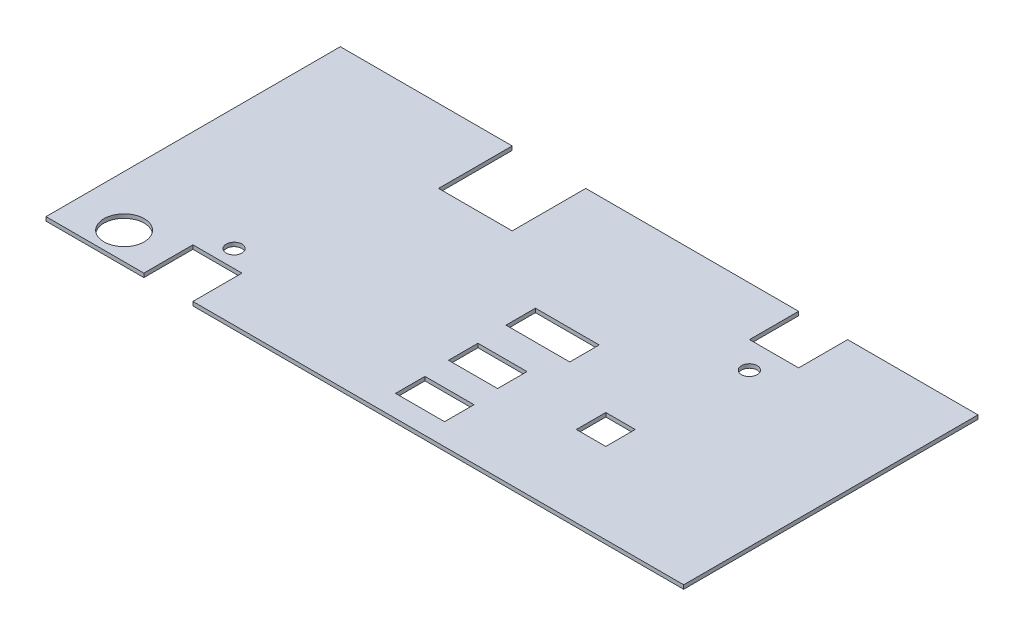
SolidWorks part; units mm, degrees
ref_plane "Front Plane" through (0, 0, 0) normal (0, 0, 1) x (1, 0, 0)
ref_plane "Top Plane" through (0, 0, 0) normal (0, 1, 0) x (1, 0, 0)
ref_plane "Right Plane" through (0, 0, 0) normal (1, 0, 0) x (0, 0, -1)
sketch "Sketch1" plane through (0, 0, 0) normal (0, 1, 0) x (1, 0, 0)
  line L1 (-65, 30) -> (65, 30)
  line L2 (-65, 30) -> (-65, -30)
  line L3 (-65, -30) -> (65, -30)
  line L4 (65, 30) -> (65, -30)
  line L5 (-65, 30) -> (65, -30) construction
  line L6 (-65, -30) -> (65, 30) construction
  point P0 (0, 0)
  dimension "D1" = 60
  dimension "D2" = 130
extrude "Boss-Extrude1" add sketch "Sketch1" along normal blind 0.8
sketch "Sketch2" plane through (0, 0, 0) normal (0, 1, 0) x (1, 0, 0)
  line L0 (-65, -30) -> (65, -30) construction
  line L1 (-45.0488, -20) -> (-35.0488, -20)
  line L2 (-45.0488, -20) -> (-45.0488, -30)
  line L3 (-45.0488, -30) -> (-35.0488, -30)
  line L4 (-35.0488, -20) -> (-35.0488, -30)
  line L5 (-45.0488, -20) -> (-35.0488, -30) construction
  line L6 (-45.0488, -30) -> (-35.0488, -20) construction
  line L7 (65, 30) -> (-65, 30) construction
  line L8 (28.4256, 30.0049) -> (38.4256, 30.0049)
  line L9 (28.4256, 30.0049) -> (28.4256, 20.0049)
  line L10 (28.4256, 20.0049) -> (38.4256, 20.0049)
  line L11 (38.4256, 30.0049) -> (38.4256, 20.0049)
  line L12 (28.4256, 30.0049) -> (38.4256, 20.0049) construction
  line L13 (28.4256, 20.0049) -> (38.4256, 30.0049) construction
  line L14 (-29.9609, 30) -> (-14.9609, 30)
  line L15 (-29.9609, 30) -> (-29.9609, 15)
  line L16 (-29.9609, 15) -> (-14.9609, 15)
  line L17 (-14.9609, 30) -> (-14.9609, 15)
  line L18 (-29.9609, 30) -> (-14.9609, 15) construction
  line L19 (-29.9609, 15) -> (-14.9609, 30) construction
  point P0 (-40.0488, -25)
  point P7 (33.4256, 25.0049)
  point P12 (-22.4609, 22.5)
  dimension "D1" = 15
  dimension "D2" = 15
  dimension "D3" = 10
  dimension "D4" = 10
  dimension "D5" = 10
  dimension "D6" = 10
extrude "Cut-Extrude5" cut sketch "Sketch2" along normal blind 3
sketch "Sketch3" plane through (0, 0.8, 0) normal (0, 1, 0) x (1, 0, 0)
  circle A0 centre (-40.1851, -16.4678) radius 1.6
  circle A1 centre (33.7948, 14.5908) radius 1.6
  circle A2 centre (-54.636, -24.4481) radius 4.1
extrude "Cut-Extrude6" cut sketch "Sketch3" against normal blind 3
sketch "Sketch4" plane through (0, 0, 0) normal (0, 1, 0) x (1, 0, 0)
  line L1 (1.0476, 3.7286) -> (14.0476, 3.7286)
  line L2 (1.0476, 3.7286) -> (1.0476, -2.2714)
  line L3 (1.0476, -2.2714) -> (14.0476, -2.2714)
  line L4 (14.0476, 3.7286) -> (14.0476, -2.2714)
  line L5 (1.0476, 3.7286) -> (14.0476, -2.2714) construction
  line L6 (1.0476, -2.2714) -> (14.0476, 3.7286) construction
  line L7 (1.3861, -8.3271) -> (11.3861, -8.3271)
  line L8 (1.3861, -8.3271) -> (1.3861, -14.3271)
  line L9 (1.3861, -14.3271) -> (11.3861, -14.3271)
  line L10 (11.3861, -8.3271) -> (11.3861, -14.3271)
  line L11 (1.3861, -8.3271) -> (11.3861, -14.3271) construction
  line L12 (1.3861, -14.3271) -> (11.3861, -8.3271) construction
  line L13 (1.8309, -19.5801) -> (11.8309, -19.5801)
  line L14 (1.8309, -19.5801) -> (1.8309, -25.5801)
  line L15 (1.8309, -25.5801) -> (11.8309, -25.5801)
  line L16 (11.8309, -19.5801) -> (11.8309, -25.5801)
  line L17 (1.8309, -19.5801) -> (11.8309, -25.5801) construction
  line L18 (1.8309, -25.5801) -> (11.8309, -19.5801) construction
  line L19 (26.6403, -7.5199) -> (32.6403, -7.5199)
  line L20 (26.6403, -7.5199) -> (26.6403, -13.5199)
  line L21 (26.6403, -13.5199) -> (32.6403, -13.5199)
  line L22 (32.6403, -7.5199) -> (32.6403, -13.5199)
  line L23 (26.6403, -7.5199) -> (32.6403, -13.5199) construction
  line L24 (26.6403, -13.5199) -> (32.6403, -7.5199) construction
  point P0 (7.5476, 0.7286)
  point P5 (6.3861, -11.3271)
  point P10 (6.8309, -22.5801)
  point P15 (29.6403, -10.5199)
  dimension "D1" = 6
  dimension "D2" = 6
  dimension "D3" = 13
  dimension "D4" = 6
  dimension "D5" = 6
  dimension "D6" = 10
  dimension "D7" = 6
  dimension "D8" = 10
extrude "Cut-Extrude8" cut sketch "Sketch4" along normal blind 3
